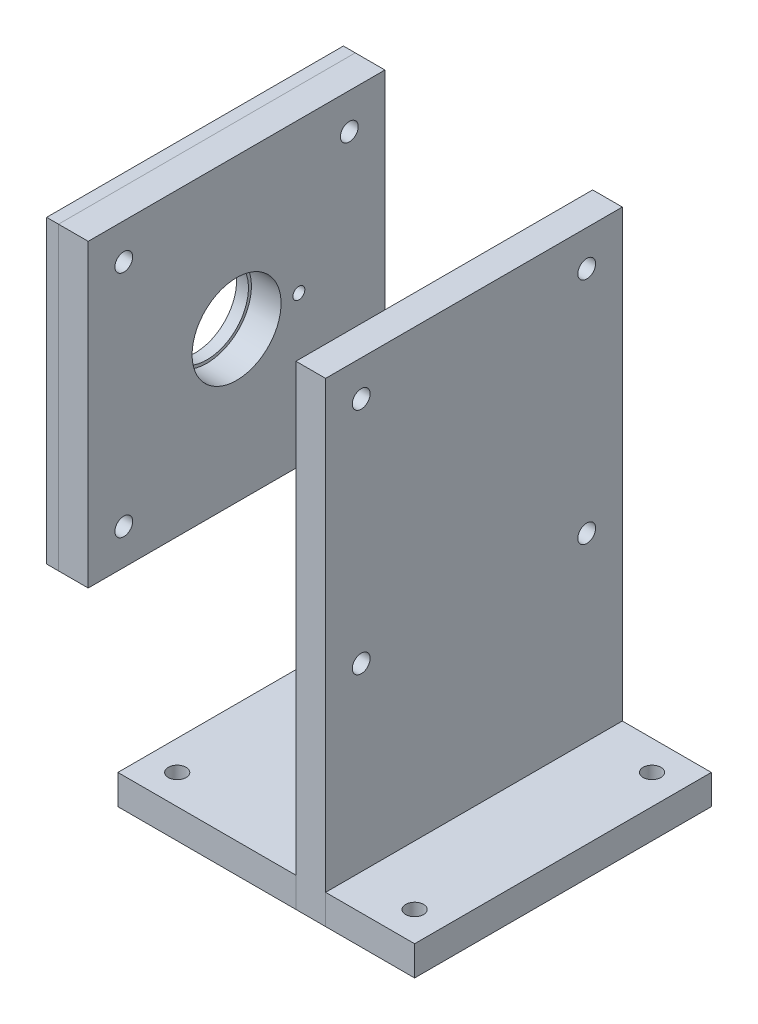
SolidWorks part; units mm, degrees
ref_plane "Front Plane" through (0, 0, 0) normal (0, 0, 1) x (1, 0, 0)
ref_plane "Top Plane" through (0, 0, 0) normal (0, 1, 0) x (1, 0, 0)
ref_plane "Right Plane" through (0, 0, 0) normal (1, 0, 0) x (0, 0, -1)
sketch "Sketch1" plane through (0, 0, 0) normal (1, 0, 0) x (0, 0, -1)
  line L0 (0, 0) -> (0, 54.7)
  line L1 (0, 0) -> (-25, 0)
  line L2 (-25, 0) -> (-25, 80)
  line L3 (-25, 80) -> (25, 80)
  line L4 (25, 80) -> (25, 0)
  line L5 (25, 0) -> (0, 0)
  circle A0 centre (0, 54.7) radius 7.5
  circle A1 centre (10.5, 54.7) radius 1
  dimension "D2" = 15
  dimension "D4" = 2
  dimension "D1" = 54.7
  dimension "D3" = 10.5
  dimension "D5" = 25
  dimension "D6" = 50
  dimension "D7" = 80
sketch "Sketch2" plane through (0, 0, 0) normal (1, 0, 0) x (0, 0, -1)
  line L0 (-25, 80) -> (-25, 0)
  line L1 (-25, 0) -> (25, 0)
  line L2 (25, 0) -> (25, 80)
  line L3 (25, 80) -> (-25, 80)
extrude "Boss-Extrude1" add sketch "Sketch2" along normal blind 5
sketch "Sketch3" plane through (0, 0, 0) normal (0, -1, 0) x (1, 0, 0)
  line L0 (0, 25) -> (-30, 25)
  line L1 (-30, 25) -> (-30, -25)
  line L2 (0, -25) -> (-30, -25)
  line L3 (0, -25) -> (20, -25)
  line L4 (20, -25) -> (20, 25)
  line L5 (20, 25) -> (0, 25)
  line L6 (5, 22.1375) -> (5, -19.0315)
  line L8 (5, -25) -> (5, 25) construction
  line L9 (5, -19.0315) -> (0, -19.0315)
  line L10 (0, -25) -> (0, 0) construction
  line L11 (0, -19.0315) -> (0, 22.1375)
  line L12 (0, 0) -> (0, 25) construction
  line L13 (0, 22.1375) -> (5, 22.1375)
  circle A0 centre (-25, 20) radius 1.5
  circle A1 centre (15, 20) radius 1.5
  circle A2 centre (15, -20) radius 1.5
  circle A3 centre (-25, -20) radius 1.5
  dimension "D3" = 3
  dimension "D6" = 3
  dimension "D1" = 20
  dimension "D2" = 30
  dimension "D4" = 5
  dimension "D5" = 5
  dimension "D7" = 5
  dimension "D8" = 5
extrude "Boss-Extrude2" add sketch "Sketch3" against normal blind 5 separate body
sketch "Sketch4" plane through (0, 0, 0) normal (0, -1, 0) x (1, 0, 0)
  line L0 (0, 25) -> (0, -25)
  line L1 (0, 25) -> (0, -25) construction
ref_plane "Plane1" through (-35, 0, 0) normal (-1, 0, 0) x (0, 0, 1)
sketch "Sketch6" plane through (-35, 0, 0) normal (-1, 0, 0) x (0, 0, 1)
  line L1 (-25, 29.4) -> (25, 29.4)
  line L2 (-25, 29.4) -> (-25, 80)
  line L3 (-25, 80) -> (25, 80)
  line L4 (25, 29.4) -> (25, 80)
  line L5 (-25, 29.4) -> (25, 80) construction
  line L6 (-25, 80) -> (25, 29.4) construction
  circle A0 centre (0, 54.7) radius 7.5
  circle A1 centre (-10.5, 54.7) radius 1 construction
  circle A2 centre (-10.5, 54.7) radius 1
  dimension "D1" = 15
  dimension "D2" = 50
extrude "Boss-Extrude3" add sketch "Sketch6" along normal blind 5 separate body
sketch "Sketch7" plane through (-40, 0, 0) normal (-1, 0, 0) x (0, 0, 1)
  line L0 (25, 80) -> (-25, 80) construction
  line L1 (-25, 80) -> (-25, 0) construction
  circle A0 centre (-19, 74) radius 1.5
  circle A1 centre (19, 74) radius 1.5
  circle A2 centre (19, 35.4) radius 1.5
  circle A3 centre (-19, 35.4) radius 1.5
  dimension "D1" = 3
  dimension "D2" = 6
  dimension "D3" = 6
extrude "Cut-Extrude1" cut sketch "Sketch7" against normal through all
sketch "Sketch8" plane through (-40, 0, 0) normal (-1, 0, 0) x (0, 0, 1)
  line L0 (-25, 80) -> (25, 80)
  line L1 (25, 80) -> (25, 29.4)
  line L2 (25, 29.4) -> (-25, 29.4)
  line L3 (-25, 29.4) -> (-25, 80)
  circle A0 centre (-19, 74) radius 1.5 construction
  circle A1 centre (19, 74) radius 1.5 construction
  circle A2 centre (19, 35.4) radius 1.5 construction
  circle A3 centre (-19, 35.4) radius 1.5 construction
  circle A4 centre (-19, 74) radius 1.5
  circle A5 centre (19, 74) radius 1.5
  circle A6 centre (19, 35.4) radius 1.5
  circle A7 centre (-19, 35.4) radius 1.5
  circle A8 centre (0, 54.7) radius 7
  circle A9 centre (-10.5, 54.7) radius 1 construction
  circle A10 centre (-10.5, 54.7) radius 1
  dimension "D1" = 14
extrude "Boss-Extrude4" add sketch "Sketch8" along normal blind 2 separate body
